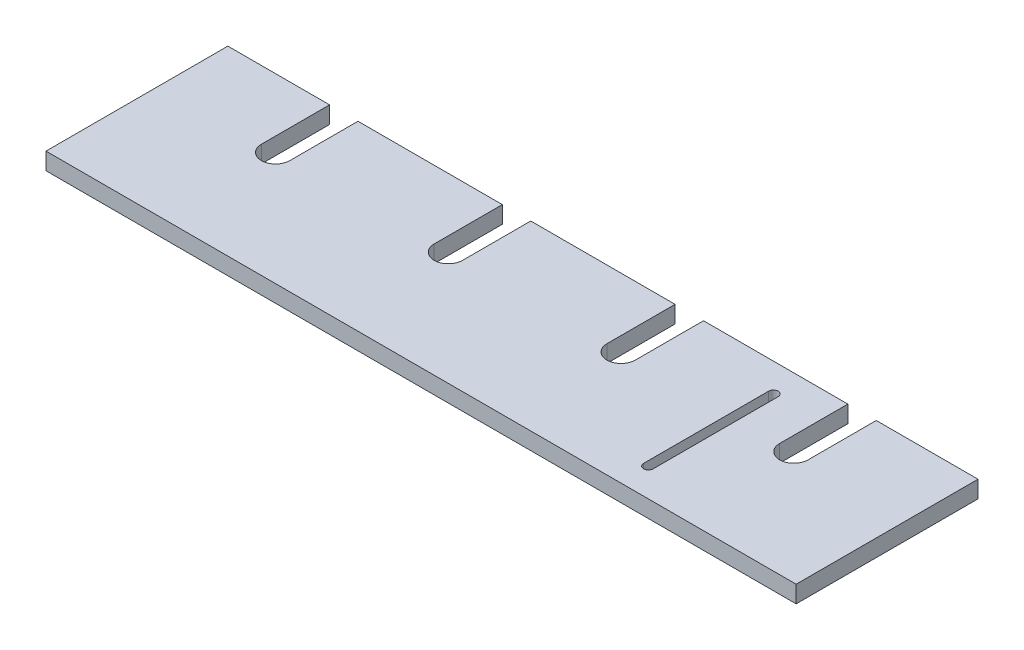
SolidWorks part; units mm, degrees
material "Acrylic (Medium-high impact)"
ref_plane "Front Plane" through (0, 0, 0) normal (0, 0, 1) x (1, 0, 0)
ref_plane "Top Plane" through (0, 0, 0) normal (0, 1, 0) x (1, 0, 0)
ref_plane "Right Plane" through (0, 0, 0) normal (1, 0, 0) x (0, 0, -1)
sketch "Sketch1" plane through (0, 0, 0) normal (0, 1, 0) x (1, 0, 0)
  line L1 (-88.9, -50.8) -> (88.9, -50.8)
  line L2 (-88.9, -50.8) -> (-88.9, 50.8)
  line L3 (-88.9, 50.8) -> (88.9, 50.8)
  line L4 (88.9, -50.8) -> (88.9, 50.8)
  line L5 (-88.9, -50.8) -> (88.9, 50.8) construction
  line L6 (-88.9, 50.8) -> (88.9, -50.8) construction
  line L7 (12.7, -50.8) -> (-190.5, -50.8)
  line L11 (-444.5, -50.8) -> (-292.1, -50.8)
  point P0 (0, 0)
  dimension "D1" = 177.8
  dimension "D2" = 101.6
extrude "Boss-Extrude1" [suppressed] add sketch "Sketch1" along normal mid plane 9.525 contours L1 L4 L3 L2
sketch "Sketch2" [suppressed] plane through (0, 0, 0) normal (0, 1, 0) x (1, 0, 0)
  line L0 (-250.825, -28.575) -> (250.825, -28.575) construction
  line L1 (161.925, -28.575) -> (60.325, -28.575)
  line L2 (161.925, -28.575) -> (161.925, -92.075)
  line L3 (161.925, -92.075) -> (60.325, -92.075)
  line L4 (60.325, -28.575) -> (60.325, -92.075)
  line L5 (0, -5.2388) -> (0, 5.2388) construction
  line L6 (-79.375, -28.575) -> (-168.275, -28.575)
  line L7 (-79.375, -28.575) -> (-79.375, -92.075)
  line L8 (-79.375, -92.075) -> (-168.275, -92.075)
  line L9 (-168.275, -28.575) -> (-168.275, -92.075)
  line L10 (250.825, -28.575) -> (250.825, 28.575) construction
  line L11 (-250.825, -28.575) -> (-250.825, 28.575) construction
  line L12 (-250.825, 28.575) -> (250.825, 28.575) construction
  line L13 (250.825, -28.575) -> (250.825, 28.575) construction
  line L14 (161.925, -28.575) -> (250.825, -28.575)
  line L15 (161.925, -28.575) -> (161.925, -71.755)
  line L16 (161.925, -71.755) -> (250.825, -71.755)
  line L17 (250.825, -28.575) -> (250.825, -71.755)
  line L18 (-250.825, -28.575) -> (-250.825, 28.575) construction
  line L19 (-79.375, -28.575) -> (60.325, -28.575)
  line L20 (-79.375, -28.575) -> (-79.375, -53.975)
  line L21 (-79.375, -53.975) -> (60.325, -53.975)
  line L22 (60.325, -28.575) -> (60.325, -53.975)
  line L23 (-168.275, -28.575) -> (-250.825, -28.575)
  line L24 (-168.275, -28.575) -> (-168.275, -71.755)
  line L25 (-168.275, -71.755) -> (-250.825, -71.755)
  line L26 (-250.825, -28.575) -> (-250.825, -71.755)
  point P19 (60.325, -92.075)
  dimension "D1" = 139.7
  dimension "D2" = 88.9
  dimension "D3" = 82.55
  dimension "D4" = 79.375
  dimension "D5" = 120.65
  dimension "D6" = 43.18
  dimension "D7" = 25.4
  dimension "D8" = 43.18
extrude "Boss-Extrude2" [suppressed] add sketch "Sketch2" along normal mid plane 9.525 contours L6 L9 L8 L7 | L23 L26 L25 L9 | L7 L21 L4 L19 | L17 L14 L2 L16
sketch "Sketch3" [suppressed] plane through (0, 4.7625, 0) normal (0, 1, 0) x (1, 0, 0)
  line L0 (-149.225, 247.65) -> (149.225, 247.65) construction
  line L1 (-98.425, 12.7) -> (98.425, 12.7)
  line L2 (-98.425, 12.7) -> (-98.425, -101.6)
  line L3 (-98.425, -101.6) -> (98.425, -101.6)
  line L4 (98.425, 12.7) -> (98.425, -101.6)
  line L5 (-98.425, 12.7) -> (98.425, -101.6) construction
  line L6 (-98.425, -101.6) -> (98.425, 12.7) construction
  line L7 (-149.225, -247.65) -> (149.225, -247.65) construction
  point P0 (0, -44.45)
  point P7 (0, 247.65)
  point P8 (0, 12.7)
  dimension "D1" = 196.85
  dimension "D2" = 114.3
  dimension "D3" = 203.2
extrude "Cut-Extrude1" [suppressed] cut sketch "Sketch3" against normal through all and the other way through all
sketch "Sketch4" [suppressed] plane through (0, -4.7625, 0) normal (0, -1, 0) x (1, 0, 0)
  line L0 (-107.315, 31.75) -> (107.315, 31.75) construction
  line L1 (-107.315, 33.9979) -> (107.315, 33.9979)
  line L2 (-107.315, 29.5021) -> (107.315, 29.5021)
  line L3 (-107.315, 6.35) -> (107.315, 6.35) construction
  line L4 (-107.315, 8.5979) -> (107.315, 8.5979)
  line L5 (-107.315, 4.1021) -> (107.315, 4.1021)
  arc A0 (-107.315, 33.9979) -> (-107.315, 29.5021) centre (-107.315, 31.75) ccw
  arc A1 (107.315, 29.5021) -> (107.315, 33.9979) centre (107.315, 31.75) ccw
  arc A2 (-107.315, 8.5979) -> (-107.315, 4.1021) centre (-107.315, 6.35) ccw
  arc A3 (107.315, 4.1021) -> (107.315, 8.5979) centre (107.315, 6.35) ccw
  point P0 (-107.315, 31.75)
  point P1 (107.315, 31.75)
  point P3 (107.315, 6.35)
  point P5 (-107.315, 6.35)
  point P10 (0, 31.75)
  point P15 (0, 6.35)
  dimension "D1" = 4.4958
  dimension "D2" = 4.4958
extrude "Cut-Extrude2" [suppressed] cut sketch "Sketch4" against normal through all
sketch "Sketch5" [suppressed] plane through (0, -4.7625, 0) normal (0, -1, 0) x (1, 0, 0)
  line L0 (69.85, 79.375) -> (69.85, -9.525) construction
  line L1 (60.325, 53.975) -> (60.325, 92.075) construction
  line L2 (161.925, 92.075) -> (60.325, 92.075) construction
  line L3 (-247.65, -22.225) -> (247.65, -22.225) construction
  line L4 (69.85, 79.375) -> (69.85, -9.525) construction
  line L5 (72.0979, 79.375) -> (72.0979, -9.525)
  line L6 (67.6021, 79.375) -> (67.6021, -9.525)
  line L7 (-88.9, 79.375) -> (-88.9, -9.525) construction
  line L8 (-79.375, 53.975) -> (-79.375, 92.075) construction
  line L9 (-79.375, 92.075) -> (-168.275, 92.075) construction
  line L10 (-88.9, 79.375) -> (-88.9, -9.525) construction
  line L11 (-86.6521, 79.375) -> (-86.6521, -9.525)
  line L12 (-91.1479, 79.375) -> (-91.1479, -9.525)
  arc A0 (72.0979, 79.375) -> (67.6021, 79.375) centre (69.85, 79.375) ccw
  arc A1 (67.6021, -9.525) -> (72.0979, -9.525) centre (69.85, -9.525) ccw
  arc A2 (-86.6521, 79.375) -> (-91.1479, 79.375) centre (-88.9, 79.375) ccw
  arc A3 (-91.1479, -9.525) -> (-86.6521, -9.525) centre (-88.9, -9.525) ccw
  point P8 (69.85, 34.925)
  point P19 (-88.9, 34.925)
  dimension "D1" = 9.525
  dimension "D2" = 12.7
  dimension "D3" = 12.7
  dimension "D4" = 4.4958
  dimension "D5" = 9.525
  dimension "D6" = 12.7
  dimension "D7" = 12.7
  dimension "D8" = 4.4958
extrude "Cut-Extrude3" [suppressed] cut sketch "Sketch5" against normal through all contours L12 A3 L11 A2 | L6 A1 L5 A0
sketch "Sketch6" [suppressed] plane through (0, 4.7625, 0) normal (0, 1, 0) x (1, 0, 0)
  line L0 (-79.375, -38.1) -> (-79.375, 38.1) construction
  line L1 (-88.9, -50.8) -> (-88.9, 50.8) construction
  line L2 (-88.9, -50.8) -> (88.9, -50.8) construction
  line L3 (-88.9, 50.8) -> (88.9, 50.8) construction
  line L4 (79.375, -38.1) -> (79.375, 38.1) construction
  line L5 (88.9, -50.8) -> (88.9, 50.8) construction
  line L6 (-79.375, -38.1) -> (-79.375, 38.1) construction
  line L7 (-81.6229, -38.1) -> (-81.6229, 38.1)
  line L8 (-77.1271, -38.1) -> (-77.1271, 38.1)
  line L9 (79.375, -38.1) -> (79.375, 38.1) construction
  line L10 (77.1271, -38.1) -> (77.1271, 38.1)
  line L11 (81.6229, -38.1) -> (81.6229, 38.1)
  arc A0 (-81.6229, -38.1) -> (-77.1271, -38.1) centre (-79.375, -38.1) ccw
  arc A1 (-77.1271, 38.1) -> (-81.6229, 38.1) centre (-79.375, 38.1) ccw
  arc A2 (77.1271, -38.1) -> (81.6229, -38.1) centre (79.375, -38.1) ccw
  arc A3 (81.6229, 38.1) -> (77.1271, 38.1) centre (79.375, 38.1) ccw
  point P12 (-79.375, 0)
  point P17 (79.375, 0)
  dimension "D1" = 9.525
  dimension "D2" = 12.7
  dimension "D3" = 12.7
  dimension "D4" = 9.525
  dimension "D5" = 12.7
  dimension "D6" = 12.7
  dimension "D7" = 4.4958
  dimension "D8" = 4.4958
extrude "Cut-Extrude4" [suppressed] cut sketch "Sketch6" against normal through all
sketch "Sketch7" [suppressed] plane through (0, 4.7625, 0) normal (0, 1, 0) x (1, 0, 0)
  point P0 (115.1313, 66.802)
  point P1 (139.827, 42.1063)
  point P3 (-139.827, 42.1063)
  point P5 (-115.1313, 66.802)
hole_wizard "#12 Clearance Hole1" [suppressed] positions "Sketch8" profile "Sketch9" hole size "#12" standard "ANSI Inch"
sketch "Sketch8" [suppressed] plane through (0, 4.7625, 0) normal (0, 1, 0) x (1, 0, 0)
  point P0 (-139.827, 42.1063)
  point P3 (-115.1313, 66.802)
  point P6 (115.1313, 66.802)
  point P9 (139.827, 42.1063)
sketch "Sketch9" plane through (-139.827, 4.7625, -42.1063) normal (1, 0, 0) x (0, 0, 1)
  line L0 (0, 0) -> (0, 18.1964)
  line L1 (0, 18.1964) -> (2.8067, 16.51)
  line L2 (2.8067, 16.51) -> (2.8067, 0)
  line L5 (2.8067, 0) -> (0, 0)
  line L10 (0, 18.1964) -> (-2.8067, 16.51) construction
  line L11 (0, -6.35) -> (0, 107.95) construction
  dimension "Hole Dia." = 5.6134
  dimension "Hole Depth" = 16.51
  dimension "Drill Angle" = 118
sketch "Sketch10" [suppressed] plane through (0, -4.7625, 0) normal (0, -1, 0) x (1, 0, 0)
  point P0 (223.8375, -6.35)
  point P1 (223.8375, 19.05)
  point P3 (-223.8375, 19.05)
  point P5 (-223.8375, -6.35)
hole_wizard "#12 Clearance Hole3" [suppressed] positions "Sketch11" profile "Sketch12" hole size "#12" standard "ANSI Inch"
sketch "Sketch11" [suppressed] plane through (0, -4.7625, 0) normal (0, -1, 0) x (-1, 0, 0)
  point P0 (-223.8375, -19.05)
  point P3 (-223.8375, 6.35)
  point P6 (223.8375, -19.05)
  point P9 (223.8375, 6.35)
sketch "Sketch12" plane through (223.8375, -4.7625, 19.05) normal (1, 0, 0) x (0, 0, -1)
  line L0 (0, 0) -> (0, 18.1964)
  line L1 (0, 18.1964) -> (2.8067, 16.51)
  line L2 (2.8067, 16.51) -> (2.8067, 0)
  line L5 (2.8067, 0) -> (0, 0)
  line L10 (0, 18.1964) -> (-2.8067, 16.51) construction
  line L11 (0, -6.35) -> (0, 107.95) construction
  dimension "Hole Dia." = 5.6134
  dimension "Hole Depth" = 16.51
  dimension "Drill Angle" = 118
sketch "Sketch13" [suppressed] plane through (0, -4.7625, 0) normal (0, -1, 0) x (1, 0, 0)
  point P0 (133.35, -223.8375)
  point P1 (107.95, -223.8375)
  point P3 (-107.95, -223.8375)
  point P5 (-133.35, -223.8375)
  point P7 (133.35, 223.8375)
  point P9 (107.95, 223.8375)
  point P11 (-107.95, 223.8375)
  point P13 (-133.35, 223.8375)
hole_wizard "#12 Clearance Hole2" [suppressed] positions "Sketch14" profile "Sketch15" hole size "#12" standard "ANSI Inch"
sketch "Sketch14" [suppressed] plane through (0, -4.7625, 0) normal (0, -1, 0) x (-1, 0, 0)
  point P0 (107.95, -223.8375)
  point P3 (133.35, -223.8375)
  point P6 (133.35, 223.8375)
  point P9 (107.95, 223.8375)
  point P12 (-133.35, 223.8375)
  point P15 (-107.95, 223.8375)
  point P18 (-133.35, -223.8375)
  point P21 (-107.95, -223.8375)
sketch "Sketch15" plane through (-107.95, -4.7625, 223.8375) normal (1, 0, 0) x (0, 0, -1)
  line L0 (0, 0) -> (0, 18.1964)
  line L1 (0, 18.1964) -> (2.8067, 16.51)
  line L2 (2.8067, 16.51) -> (2.8067, 0)
  line L5 (2.8067, 0) -> (0, 0)
  line L10 (0, 18.1964) -> (-2.8067, 16.51) construction
  line L11 (0, -6.35) -> (0, 107.95) construction
  dimension "Hole Dia." = 5.6134
  dimension "Hole Depth" = 16.51
  dimension "Drill Angle" = 118
sketch "Sketch16" [suppressed] plane through (0, 4.7625, 0) normal (0, 1, 0) x (1, 0, 0)
  line L0 (88.9, -50.8) -> (88.9, 50.8) construction
  line L1 (-88.9, -50.8) -> (-88.9, 50.8) construction
  line L2 (-88.9, -50.8) -> (88.9, -50.8) construction
  point P0 (79.375, -38.1)
  point P1 (-79.375, -38.1)
  dimension "D1" = 9.525
  dimension "D2" = 9.525
  dimension "D3" = 12.7
hole_wizard "#8 Clearance Hole1" [suppressed] positions "Sketch17" profile "Sketch19" hole size "#8" standard "ANSI Inch"
sketch "Sketch17" [suppressed] plane through (0, 4.7625, 0) normal (0, 1, 0) x (1, 0, 0)
  point P0 (79.375, -38.1)
  point P3 (-79.375, -38.1)
sketch "Sketch19" plane through (79.375, 4.7625, 38.1) normal (1, 0, 0) x (0, 0, 1)
  line L0 (0, 0) -> (0, 12.0187)
  line L1 (0, 12.0187) -> (2.2479, 10.668)
  line L2 (2.2479, 10.668) -> (2.2479, 0)
  line L5 (2.2479, 0) -> (0, 0)
  line L10 (0, 12.0187) -> (-2.2479, 10.668) construction
  line L11 (0, -6.35) -> (0, 107.95) construction
  dimension "Hole Dia." = 4.4958
  dimension "Hole Depth" = 10.668
  dimension "Drill Angle" = 118
sketch "Sketch20" [suppressed] plane through (0, -4.7625, 0) normal (0, -1, 0) x (1, 0, 0)
  line L0 (-149.225, 247.65) -> (149.225, 247.65) construction
  line L1 (23.9395, 147.5105) -> (-23.9395, 147.5105)
  line L2 (23.9395, 147.5105) -> (23.9395, 195.3895)
  line L3 (23.9395, 195.3895) -> (-23.9395, 195.3895)
  line L4 (-23.9395, 147.5105) -> (-23.9395, 195.3895)
  line L5 (23.9395, 147.5105) -> (-23.9395, 195.3895) construction
  line L6 (23.9395, 195.3895) -> (-23.9395, 147.5105) construction
  line L8 (38.1, 155.575) -> (-38.1, 155.575) construction
  line L9 (38.1, 155.575) -> (38.1, 187.325) construction
  line L10 (38.1, 187.325) -> (-38.1, 187.325) construction
  line L11 (-38.1, 155.575) -> (-38.1, 187.325) construction
  point P0 (0, 171.45)
  point P7 (0, 247.65)
  point P8 (38.1, 155.575)
  point P9 (38.1, 187.325)
  point P10 (-38.1, 155.575)
  point P11 (-38.1, 187.325)
  point P18 (0, 187.325)
  point P19 (0, 195.3895)
  point P20 (-38.1, 171.45)
  point P21 (-23.9395, 171.45)
  dimension "D1" = 47.879
  dimension "D2" = 47.879
  dimension "D3" = 38.1
  dimension "D4" = 15.875
  dimension "D5" = 76.2
extrude "Cut-Extrude5" [suppressed] cut sketch "Sketch20" against normal through all contours L1 L4 L3 L2
hole_wizard "#10 Clearance Hole1" [suppressed] positions "Sketch21" profile "Sketch22" hole size "#10" standard "ANSI Inch"
sketch "Sketch21" [suppressed] plane through (0, -4.7625, 0) normal (0, -1, 0) x (-1, 0, 0)
  point P0 (-38.1, -155.575)
  point P3 (38.1, -155.575)
  point P6 (38.1, -187.325)
  point P9 (-38.1, -187.325)
sketch "Sketch22" plane through (38.1, -4.7625, 155.575) normal (1, 0, 0) x (0, 0, -1)
  line L0 (0, 0) -> (0, 12.2018)
  line L1 (0, 12.2018) -> (2.5527, 10.668)
  line L2 (2.5527, 10.668) -> (2.5527, 0)
  line L5 (2.5527, 0) -> (0, 0)
  line L10 (0, 12.2018) -> (-2.5527, 10.668) construction
  line L11 (0, -6.35) -> (0, 107.95) construction
  dimension "Hole Dia." = 5.1054
  dimension "Hole Depth" = 10.668
  dimension "Drill Angle" = 118
sketch "Sketch23" [suppressed] plane through (-250.825, 0, 0) normal (-1, 0, 0) x (0, 0, 1)
  line L4 (-28.575, -4.7625) -> (71.755, -4.7625)
  line L5 (71.755, -4.7625) -> (71.755, 4.7625)
  line L6 (71.755, 4.7625) -> (-28.575, 4.7625)
  line L7 (-28.575, 4.7625) -> (-28.575, -4.7625)
  line L8 (-28.575, -4.7625) -> (71.755, -4.7625)
  line L9 (71.755, -4.7625) -> (71.755, 4.7625)
  line L10 (71.755, 4.7625) -> (-28.575, 4.7625)
  line L11 (-28.575, 4.7625) -> (-28.575, -4.7625)
  dimension "D1" = 0
extrude "Boss-Extrude3" [suppressed] add sketch "Sketch23" along normal blind 6.35
mirror "Mirror1" [suppressed] about plane through (0, 0, 0) normal (1, 0, 0)
sketch "Sketch27" [suppressed] plane through (0, 4.7625, 0) normal (0, 1, 0) x (1, 0, 0)
  line L1 (257.175, -71.755) -> (257.175, 28.575) construction
  line L2 (-257.175, 28.575) -> (257.175, 28.575) construction
  point P0 (241.3, 12.7)
  dimension "D1" = 15.875
  dimension "D2" = 15.875
hole_wizard "#10 Clearance Hole2" [suppressed] positions "Sketch28" profile "Sketch30" hole size "#10" standard "ANSI Inch"
sketch "Sketch28" [suppressed] plane through (0, 4.7625, 0) normal (0, 1, 0) x (1, 0, 0)
  point P0 (241.3, 12.7)
sketch "Sketch30" plane through (241.3, 4.7625, -12.7) normal (1, 0, 0) x (0, 0, 1)
  line L0 (0, 0) -> (0, 9.525)
  line L1 (0, 9.525) -> (2.5527, 9.525)
  line L2 (2.5527, 9.525) -> (2.5527, 0)
  line L5 (2.5527, 0) -> (0, 0)
  line L11 (0, -6.35) -> (0, 107.95) construction
  dimension "Thru Hole Dia." = 5.1054
  dimension "Thru Hole Depth" = 9.525
pattern_linear "LPattern1" [suppressed] count 6 spacing 96.52
sketch "Sketch31" [suppressed] plane through (0, 4.7625, 0) normal (0, 1, 0) x (1, 0, 0)
  line L1 (0, -5.2388) -> (0, 5.2388) construction
  line L2 (-149.225, 76.2) -> (149.225, 76.2) construction
  point P0 (-95.25, 60.325)
  dimension "D1" = 15.875
  dimension "D2" = 95.25
hole_wizard "#10 Clearance Hole3" [suppressed] positions "Sketch32" profile "Sketch33" hole size "#10" standard "ANSI Inch"
sketch "Sketch32" [suppressed] plane through (0, 4.7625, 0) normal (0, 1, 0) x (1, 0, 0)
  point P0 (-95.25, 60.325)
sketch "Sketch33" plane through (-95.25, 4.7625, -60.325) normal (1, 0, 0) x (0, 0, 1)
  line L0 (0, 0) -> (0, 9.525)
  line L1 (0, 9.525) -> (2.5527, 9.525)
  line L2 (2.5527, 9.525) -> (2.5527, 0)
  line L5 (2.5527, 0) -> (0, 0)
  line L11 (0, -6.35) -> (0, 107.95) construction
  dimension "Thru Hole Dia." = 5.1054
  dimension "Thru Hole Depth" = 9.525
pattern_linear "LPattern2" [suppressed] count 4 spacing 63.5
sketch "Sketch34" [suppressed] plane through (0, 4.7625, 0) normal (0, 1, 0) x (1, 0, 0)
  line L0 (0, -5.2388) -> (0, 5.2388) construction
  line L1 (-149.225, 247.65) -> (149.225, 247.65) construction
  point P0 (-63.5, 241.3)
  dimension "D1" = 63.5
  dimension "D2" = 6.35
hole_wizard "#10 Clearance Hole4" [suppressed] positions "Sketch35" profile "Sketch36" hole size "#10" standard "ANSI Inch"
sketch "Sketch35" [suppressed] plane through (0, 4.7625, 0) normal (0, 1, 0) x (1, 0, 0)
  point P0 (-63.5, 241.3)
sketch "Sketch36" plane through (-63.5, 4.7625, -241.3) normal (1, 0, 0) x (0, 0, 1)
  line L0 (0, 0) -> (0, 9.525)
  line L1 (0, 9.525) -> (2.5527, 9.525)
  line L2 (2.5527, 9.525) -> (2.5527, 0)
  line L5 (2.5527, 0) -> (0, 0)
  line L11 (0, -6.35) -> (0, 107.95) construction
  dimension "Thru Hole Dia." = 5.1054
  dimension "Thru Hole Depth" = 9.525
pattern_linear "LPattern3" [suppressed] count 3 spacing 63.5
mirror "Mirror2" [suppressed] about plane through (0, 0, 0) normal (0, 0, 1)
sketch "Sketch37" [suppressed] plane through (0, 4.7625, 0) normal (0, 1, 0) x (1, 0, 0)
  line L0 (-5.2388, 0) -> (5.2388, 0) construction
  line L1 (-149.225, -247.65) -> (-149.225, 247.65) construction
  point P0 (-142.875, 0)
  dimension "D1" = 6.35
hole_wizard "#10 Clearance Hole5" [suppressed] positions "Sketch38" profile "Sketch39" hole size "#10" standard "ANSI Inch"
sketch "Sketch38" [suppressed] plane through (0, 4.7625, 0) normal (0, 1, 0) x (1, 0, 0)
  point P0 (-142.875, 0)
sketch "Sketch39" plane through (-142.875, 4.7625, 0) normal (1, 0, 0) x (0, 0, 1)
  line L0 (0, 0) -> (0, 9.525)
  line L1 (0, 9.525) -> (2.5527, 9.525)
  line L2 (2.5527, 9.525) -> (2.5527, 0)
  line L5 (2.5527, 0) -> (0, 0)
  line L11 (0, -6.35) -> (0, 107.95) construction
  dimension "Thru Hole Dia." = 5.1054
  dimension "Thru Hole Depth" = 9.525
pattern_linear "LPattern4" [suppressed] count 3 spacing 96.52 count 3 spacing 96.52
mirror "Mirror3" [suppressed] about plane through (0, 0, 0) normal (1, 0, 0)
sketch "Sketch40" [suppressed] plane through (0, 4.7625, 0) normal (0, 1, 0) x (1, 0, 0)
  line L0 (-79.375, -53.975) -> (-79.375, -92.075) construction
  line L3 (-88.9, -79.375) -> (-88.9, -9.525) construction
  line L4 (-91.1479, -79.375) -> (-91.1479, -9.525)
  line L5 (-86.6521, -79.375) -> (-86.6521, -9.525)
  line L6 (69.85, -79.375) -> (69.85, -9.525) construction
  line L7 (67.6021, -79.375) -> (67.6021, -9.525)
  line L8 (72.0979, -79.375) -> (72.0979, -9.525)
  line L9 (60.325, -53.975) -> (60.325, -92.075) construction
  line L12 (-79.375, -92.075) -> (-168.275, -92.075) construction
  line L13 (161.925, -92.075) -> (60.325, -92.075) construction
  arc A2 (-91.1479, -79.375) -> (-86.6521, -79.375) centre (-88.9, -79.375) ccw
  arc A3 (-86.6521, -9.525) -> (-91.1479, -9.525) centre (-88.9, -9.525) ccw
  arc A4 (67.6021, -79.375) -> (72.0979, -79.375) centre (69.85, -79.375) ccw
  arc A5 (72.0979, -9.525) -> (67.6021, -9.525) centre (69.85, -9.525) ccw
  point P7 (-88.9, -44.45)
  point P14 (69.85, -44.45)
  dimension "D1" = 9.525
  dimension "D2" = 4.4958
  dimension "D3" = 4.4958
  dimension "D4" = 9.525
  dimension "D5" = 12.7
  dimension "D6" = 12.7
  dimension "D7" = 69.85
  dimension "D8" = 69.85
extrude "Cut-Extrude6" [suppressed] cut sketch "Sketch40" against normal up to next
sketch "Sketch41" [suppressed] plane through (0, -4.7625, 0) normal (0, -1, 0) x (1, 0, 0)
  point P0 (120.65, -32.5755)
  point P1 (-120.65, -32.5755)
  point P3 (-120.65, 121.4755)
  point P5 (120.65, 121.4755)
hole_wizard "#10 Clearance Hole6" [suppressed] positions "Sketch42" profile "Sketch43" hole size "#10" standard "ANSI Inch"
sketch "Sketch42" [suppressed] plane through (0, 4.7625, 0) normal (0, 1, 0) x (1, 0, 0)
  point P0 (120.65, 32.5755)
  point P3 (120.65, -121.4755)
  point P6 (-120.65, -121.4755)
  point P9 (-120.65, 32.5755)
sketch "Sketch43" plane through (120.65, 4.7625, -32.5755) normal (1, 0, 0) x (0, 0, 1)
  line L0 (0, 0) -> (0, 9.525)
  line L1 (0, 9.525) -> (2.5527, 9.525)
  line L2 (2.5527, 9.525) -> (2.5527, 0)
  line L5 (2.5527, 0) -> (0, 0)
  line L11 (0, -6.35) -> (0, 107.95) construction
  dimension "Thru Hole Dia." = 5.1054
  dimension "Thru Hole Depth" = 9.525
sketch "Sketch44" [suppressed] plane through (0, 4.7625, 0) normal (0, 1, 0) x (1, 0, 0)
  line L0 (0, -5.2388) -> (0, 5.2388) construction
  line L2 (120.65, 32.5755) -> (-120.65, 32.5755) construction
  line L3 (120.65, -121.4755) -> (-120.65, -121.4755) construction
  point P0 (76.2, 32.5755)
  point P1 (0, 32.5755)
  point P2 (-76.2, 32.5755)
  point P3 (76.2, -121.4755)
  point P4 (0, -121.4755)
  point P5 (-76.2, -121.4755)
  dimension "D1" = 76.2
  dimension "D2" = 76.2
hole_wizard "#10 Clearance Hole7" [suppressed] positions "Sketch45" profile "Sketch46" hole size "#10" standard "ANSI Inch"
sketch "Sketch45" [suppressed] plane through (0, 4.7625, 0) normal (0, 1, 0) x (1, 0, 0)
  point P0 (76.2, 32.5755)
  point P3 (0, 32.5755)
  point P6 (-76.2, 32.5755)
  point P9 (76.2, -121.4755)
  point P12 (0, -121.4755)
  point P15 (-76.2, -121.4755)
sketch "Sketch46" plane through (76.2, 4.7625, -32.5755) normal (1, 0, 0) x (0, 0, 1)
  line L0 (0, 0) -> (0, 9.525)
  line L1 (0, 9.525) -> (2.5527, 9.525)
  line L2 (2.5527, 9.525) -> (2.5527, 0)
  line L5 (2.5527, 0) -> (0, 0)
  line L11 (0, -6.35) -> (0, 107.95) construction
  dimension "Thru Hole Dia." = 5.1054
  dimension "Thru Hole Depth" = 9.525
sketch "Sketch47" [suppressed] plane through (0, 4.7625, 0) normal (0, 1, 0) x (1, 0, 0)
  line L1 (-142.875, 0) -> (-142.875, -96.52) construction
  line L2 (142.875, 0) -> (142.875, -96.52) construction
  point P0 (-142.875, -71.12)
  point P1 (142.875, -25.4)
  point P2 (-142.875, -25.4)
  point P3 (142.875, -71.12)
  dimension "D1" = 25.4
  dimension "D2" = 25.4
  dimension "D3" = 25.4
  dimension "D4" = 25.4
hole_wizard "#10 Clearance Hole8" [suppressed] positions "Sketch48" profile "Sketch49" hole size "#10" standard "ANSI Inch"
sketch "Sketch48" [suppressed] plane through (0, 4.7625, 0) normal (0, 1, 0) x (1, 0, 0)
  point P0 (-142.875, -71.12)
  point P3 (142.875, -25.4)
  point P7 (-142.875, -25.4)
  point P10 (142.875, -71.12)
sketch "Sketch49" plane through (-142.875, 4.7625, 71.12) normal (1, 0, 0) x (0, 0, 1)
  line L0 (0, 0) -> (0, 9.525)
  line L1 (0, 9.525) -> (2.5527, 9.525)
  line L2 (2.5527, 9.525) -> (2.5527, 0)
  line L5 (2.5527, 0) -> (0, 0)
  line L11 (0, -6.35) -> (0, 107.95) construction
  dimension "Thru Hole Dia." = 5.1054
  dimension "Thru Hole Depth" = 9.525
sketch "Sketch50" plane through (0, 0, 0) normal (0, 1, 0) x (1, 0, 0)
  line L1 (-209.55, -50.8) -> (209.55, -50.8)
  line L2 (-209.55, -50.8) -> (-209.55, 50.8)
  line L3 (-209.55, 50.8) -> (209.55, 50.8)
  line L4 (209.55, -50.8) -> (209.55, 50.8)
  line L5 (-209.55, -50.8) -> (209.55, 50.8) construction
  line L6 (-209.55, 50.8) -> (209.55, -50.8) construction
  point P0 (0, 0)
  dimension "D1" = 419.1
  dimension "D2" = 101.6
extrude "Boss-Extrude4" add sketch "Sketch50" along normal blind 9.525
sketch "Sketch51" plane through (0, 0, 0) normal (0, -1, 0) x (1, 0, 0)
  line L0 (144.78, -12.7) -> (144.78, -50.8) construction
  line L1 (152.7175, -12.7) -> (152.7175, -50.8)
  line L2 (136.8425, -12.7) -> (136.8425, -50.8)
  line L3 (209.55, -50.8) -> (-209.55, -50.8) construction
  line L4 (209.55, 50.8) -> (209.55, -50.8) construction
  line L5 (48.26, -50.8) -> (48.26, -12.7) construction
  line L7 (40.3225, -50.8) -> (40.3225, -12.7)
  line L8 (56.1975, -50.8) -> (56.1975, -12.7)
  arc A0 (152.7175, -12.7) -> (136.8425, -12.7) centre (144.78, -12.7) ccw
  arc A1 (136.8425, -50.8) -> (152.7175, -50.8) centre (144.78, -50.8) ccw
  arc A2 (40.3225, -50.8) -> (56.1975, -50.8) centre (48.26, -50.8) ccw
  arc A3 (56.1975, -12.7) -> (40.3225, -12.7) centre (48.26, -12.7) ccw
  point P2 (144.78, -31.75)
  point P7 (48.26, -31.75)
  dimension "D1" = 38.1
  dimension "D2" = 64.77
  dimension "D3" = 15.875
  dimension "D4" = 15.875
  dimension "D5" = 96.52
extrude "Cut-Extrude7" cut sketch "Sketch51" against normal up to next
mirror "Mirror4" about plane through (0, 0, 0) normal (1, 0, 0) of "Cut-Extrude7"
sketch "Sketch52" [suppressed] plane through (0, 4.7625, 0) normal (0, 1, 0) x (1, 0, 0)
  line L0 (-79.375, -92.075) -> (-168.275, -92.075) construction
  line L1 (161.925, -92.075) -> (60.325, -92.075) construction
  point P0 (-123.825, -38.1)
  point P1 (111.125, -38.1)
  point P4 (-123.825, -92.075)
  point P7 (111.125, -92.075)
  dimension "D1" = 53.975
hole_wizard "#10 Clearance Hole9" [suppressed] positions "Sketch53" profile "Sketch54" hole size "#10" standard "ANSI Inch"
sketch "Sketch53" plane through (0, 4.7625, 0) normal (0, 1, 0) x (1, 0, 0)
  point P0 (-123.825, -38.1)
  point P3 (111.125, -38.1)
sketch "Sketch54" plane through (-123.825, 4.7625, 38.1) normal (1, 0, 0) x (0, 0, 1)
  line L0 (0, 0) -> (0, 9.525)
  line L1 (0, 9.525) -> (2.5527, 9.525)
  line L2 (2.5527, 9.525) -> (2.5527, 0)
  line L5 (2.5527, 0) -> (0, 0)
  line L11 (0, -6.35) -> (0, 107.95) construction
  dimension "Thru Hole Dia." = 5.1054
  dimension "Thru Hole Depth" = 9.525
sketch "Sketch55" plane through (0, 0, 0) normal (0, -1, 0) x (1, 0, 0)
  line L0 (111.125, 34.925) -> (111.125, -34.925) construction
  line L1 (113.792, 34.925) -> (113.792, -34.925)
  line L2 (108.458, 34.925) -> (108.458, -34.925)
  line L3 (-123.825, 34.925) -> (-123.825, -34.925) construction
  line L4 (209.55, 50.8) -> (209.55, -50.8) construction
  line L5 (-121.158, 34.925) -> (-121.158, -34.925)
  line L6 (-126.492, 34.925) -> (-126.492, -34.925)
  line L7 (-209.55, -50.8) -> (-209.55, 50.8) construction
  arc A0 (113.792, 34.925) -> (108.458, 34.925) centre (111.125, 34.925) ccw
  arc A1 (108.458, -34.925) -> (113.792, -34.925) centre (111.125, -34.925) ccw
  arc A2 (-121.158, 34.925) -> (-126.492, 34.925) centre (-123.825, 34.925) ccw
  arc A3 (-126.492, -34.925) -> (-121.158, -34.925) centre (-123.825, -34.925) ccw
  point P2 (111.125, 0)
  point P11 (209.55, 0)
  point P12 (-123.825, 0)
  dimension "D1" = 5.334
  dimension "D2" = 69.85
  dimension "D3" = 98.425
  dimension "D4" = 85.725
  dimension "D5" = 5.334
  dimension "D6" = 69.85
extrude "Cut-Extrude8" cut sketch "Sketch55" against normal up to next contours L2 A1 L1 A0
sketch "Sketch56" [suppressed] plane through (0, 4.7625, 0) normal (0, 1, 0) x (1, 0, 0)
  line L0 (-257.175, -71.755) -> (-257.175, 28.575) construction
  line L1 (-168.275, -71.755) -> (-257.175, -71.755) construction
  line L2 (257.175, -71.755) -> (257.175, 28.575) construction
  line L3 (161.925, -71.755) -> (257.175, -71.755) construction
  point P0 (-234.95, -62.23)
  point P5 (234.95, -62.23)
  dimension "D1" = 22.225
  dimension "D2" = 9.525
  dimension "D3" = 22.225
  dimension "D4" = 9.525
hole_wizard "#10-32 Tapped Hole2" [suppressed] positions "Sketch57" profile "Sketch58" tap size "#10-32" standard "ANSI Inch"
sketch "Sketch57" plane through (0, 4.7625, 0) normal (0, 1, 0) x (1, 0, 0)
  point P0 (234.95, -62.23)
  point P3 (-234.95, -62.23)
sketch "Sketch58" plane through (234.95, 4.7625, 62.23) normal (1, 0, 0) x (0, 0, 1)
  line L0 (0, 0) -> (0, 9.525)
  line L1 (0, 9.525) -> (2.0193, 9.525)
  line L2 (2.0193, 9.525) -> (2.0193, 0)
  line L5 (2.0193, 0) -> (0, 0)
  line L11 (0, -6.35) -> (0, 107.95) construction
  dimension "Thru Tap Drill Dia." = 4.0386
  dimension "Thru Tap Drill Depth" = 9.525
sketch "Sketch59" [suppressed] plane through (0, 4.7625, 0) normal (0, 1, 0) x (1, 0, 0)
  line L0 (-149.225, -76.2) -> (149.225, -76.2) construction
  line L1 (149.225, -76.2) -> (149.225, 76.2) construction
  line L2 (-149.225, -76.2) -> (-149.225, 76.2) construction
  point P0 (139.7, -14.605)
  point P1 (-139.7, -14.605)
  dimension "D1" = 61.595
  dimension "D2" = 9.525
  dimension "D3" = 9.525
hole_wizard "#10-32 Tapped Hole1" [suppressed] positions "Sketch60" profile "Sketch62" tap size "#10-32" standard "ANSI Inch"
sketch "Sketch60" plane through (0, 4.7625, 0) normal (0, 1, 0) x (1, 0, 0)
  point P0 (-139.7, -14.605)
  point P3 (139.7, -14.605)
sketch "Sketch62" plane through (-139.7, 4.7625, 14.605) normal (1, 0, 0) x (0, 0, 1)
  line L0 (0, 0) -> (0, 9.525)
  line L1 (0, 9.525) -> (2.0193, 9.525)
  line L2 (2.0193, 9.525) -> (2.0193, 0)
  line L5 (2.0193, 0) -> (0, 0)
  line L11 (0, -6.35) -> (0, 107.95) construction
  dimension "Thru Tap Drill Dia." = 4.0386
  dimension "Thru Tap Drill Depth" = 9.525
cosmetic thread "Hole Thread1" [suppressed] parameters "D2"=4.826
cosmetic thread "Hole Thread2" [suppressed] parameters "D2"=4.826
sketch "Sketch63" [suppressed] plane through (0, 4.7625, 0) normal (0, 1, 0) x (1, 0, 0)
  line L0 (-149.225, 76.2) -> (149.225, 76.2) construction
  line L1 (-149.225, -76.2) -> (-149.225, 76.2) construction
  point P0 (-65.0875, 19.05)
  point P1 (-26.9875, 19.05)
  dimension "D1" = 38.1
  dimension "D2" = 57.15
  dimension "D3" = 84.1375
hole_wizard "1/4 Clearance Hole1" [suppressed] positions "Sketch64" profile "Sketch65" hole size "1/4" standard "ANSI Inch"
sketch "Sketch64" plane through (0, 4.7625, 0) normal (0, 1, 0) x (1, 0, 0)
  point P0 (-65.0875, 19.05)
  point P3 (-26.9875, 19.05)
sketch "Sketch65" plane through (-65.0875, 4.7625, -19.05) normal (1, 0, 0) x (0, 0, 1)
  line L0 (0, 0) -> (0, 9.525)
  line L1 (0, 9.525) -> (3.3782, 9.525)
  line L2 (3.3782, 9.525) -> (3.3782, 0)
  line L5 (3.3782, 0) -> (0, 0)
  line L11 (0, -6.35) -> (0, 107.95) construction
  dimension "Thru Hole Dia." = 6.7564
  dimension "Thru Hole Depth" = 9.525
mirror "Mirror5" [suppressed] about plane through (0, 0, 0) normal (1, 0, 0)
